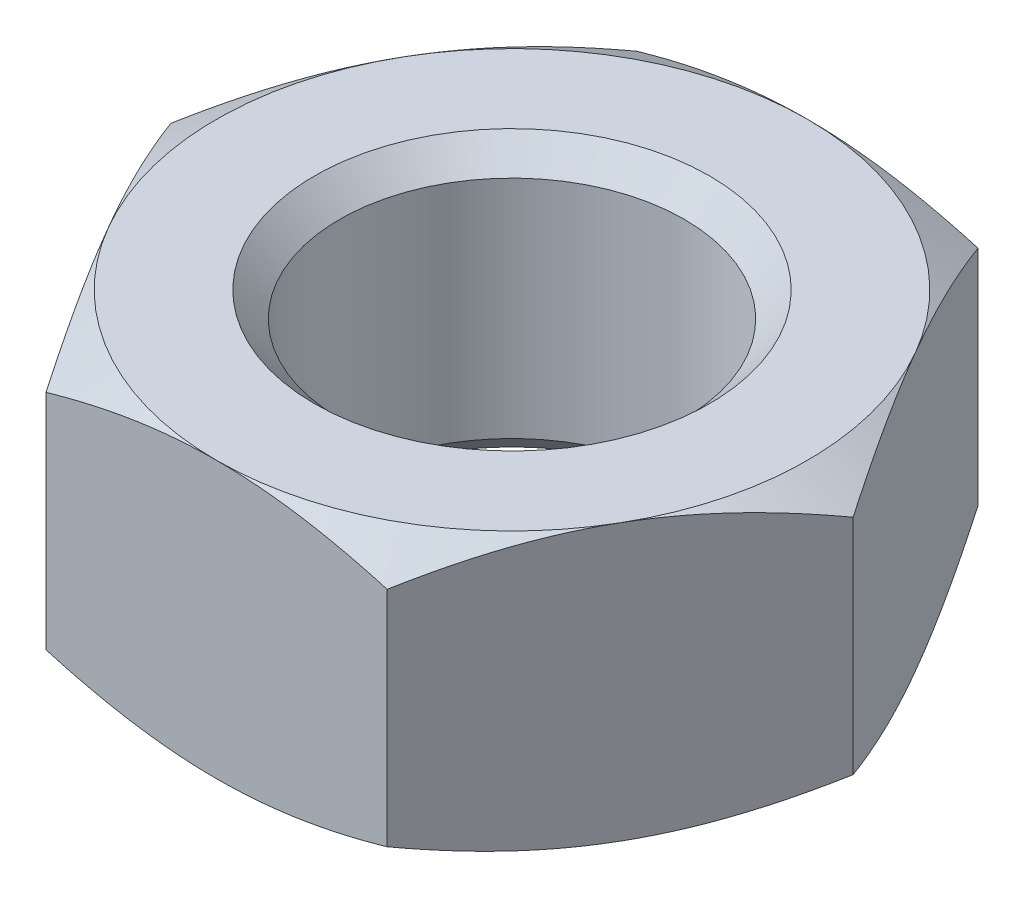
SolidWorks part; units mm, degrees
material "1.0050 (E295)"
ref_plane "Спереди" through (0, 0, 0) normal (0, 0, 1) x (1, 0, 0)
ref_plane "Сверху" through (0, 0, 0) normal (0, 1, 0) x (1, 0, 0)
ref_plane "Справа" through (0, 0, 0) normal (1, 0, 0) x (0, 0, -1)
sketch "Эскиз1" plane through (0, 0, 0) normal (0, 1, 0) x (1, 0, 0)
  line L1 (-8.6603, 15) -> (-17.3205, 0)
  line L2 (-17.3205, 0) -> (-8.6603, -15)
  line L3 (-8.6603, -15) -> (8.6603, -15)
  line L4 (8.6603, -15) -> (17.3205, 0)
  line L5 (17.3205, 0) -> (8.6603, 15)
  line L6 (8.6603, 15) -> (-8.6603, 15)
  circle A0 centre (0, 0) radius 15 construction
  dimension "D1" = 30
extrude "Бобышка-Вытянуть1" add sketch "Эскиз1" along normal blind 14
sketch "Эскиз2" plane through (0, 0, 0) normal (1, 0, 0) x (0, 0, -1)
  line L0 (-15, 14) -> (-20, 14)
  line L1 (-20, 14) -> (-20, 11.1132)
  line L2 (-20, 11.1132) -> (-15, 14)
  line L3 (0, -1000) -> (0, 49000) construction
  line L4 (-15, 0) -> (-20, 0)
  line L5 (-20, 0) -> (-20, 2.8868)
  line L6 (-20, 2.8868) -> (-15, 0)
  line L7 (-15, 14) -> (-15, 0) construction
  dimension "D1" = 30
  dimension "D2" = 5
  dimension "D3" = 30
revolve "Вырез-Повернуть1" cut sketch "Эскиз2" angle 360 about L3
hole_wizard "Отверстие обработанное метчиком M20x2.51" positions "Трехмерный эскиз1" profile "Эскиз3" tap size "M20x2.5" standard "Ansi Metric" end condition through all
sketch3d "Трехмерный эскиз1"
  point P0 (0, 0, 0)
  point P4 (0, 0, 0)
sketch "Эскиз3" plane through (0, 0, 0) normal (1, 0, 0) x (0, 0, -1)
  line L0 (0, 0) -> (0, 14)
  line L1 (0, 14) -> (10.025, 14)
  line L2 (8.75, 12.725) -> (8.75, 1.275)
  line L3 (8.75, 1.275) -> (10.025, 0)
  line L5 (10.025, 0) -> (0, 0)
  line L6 (-8.75, 1.275) -> (-10.025, 0) construction
  line L7 (10.025, 14) -> (8.75, 12.725)
  line L8 (-10.025, 14) -> (-8.75, 12.725) construction
  line L11 (0, -6.35) -> (0, 107.95) construction
  dimension "Диаметр проходного сверла" = 17.5
  dimension "Глубина проходного сверла" = 14
  dimension "Диаметр передней зенковки" = 20.05
  dimension "Угол передней зенковки" = 90
  dimension "Диаметр задней зенковки" = 20.05
  dimension "Угол задней зенковки" = 90
cosmetic thread "Отверстие резьбы1" parameters "D2"=20
cosmetic thread "Отверстие резьбы2" parameters "D2"=20
